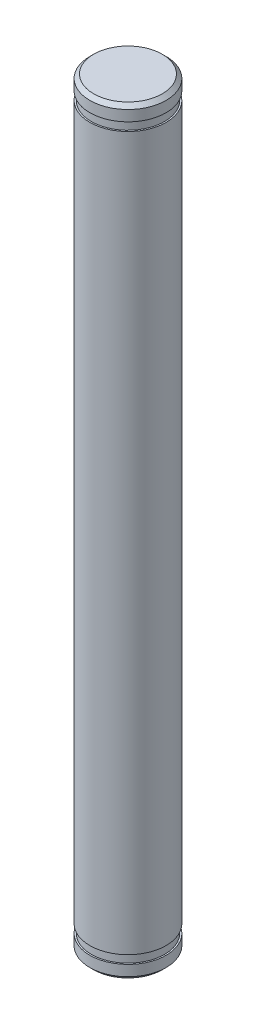
SolidWorks part; units mm, degrees
ref_plane "前视基准面" through (0, 0, 0) normal (0, 0, 1) x (1, 0, 0)
ref_plane "上视基准面" through (0, 0, 0) normal (0, 1, 0) x (1, 0, 0)
ref_plane "右视基准面" through (0, 0, 0) normal (1, 0, 0) x (0, 0, -1)
other "Configuration Table"
sketch "草图1" plane through (0, 0, 0) normal (0, 1, 0) x (1, 0, 0)
  circle A0 centre (0, 0) radius 5
  dimension "D1" = 10
extrude "凸台-拉伸1" add sketch "草图1" along normal blind 99.5
chamfer "倒角1" distance 0.5 angle 45 2 edges at (0, 0, 5) (0, 99.5, 5)
ref_plane "基准面1" through (0, 49.75, 0) normal (0, 1, 0) x (1, 0, 0)
sketch "草图2" plane through (0, 99.5, 0) normal (0, 1, 0) x (1, 0, 0)
  circle A0 centre (0, 0) radius 5 construction
  circle A1 centre (0, 0) radius 5
  circle A2 centre (0, 0) radius 4.8
  dimension "D1" = 9.6
extrude "切除-拉伸1" cut sketch "草图2" along normal blind 1.1 from offset 3 offset against normal yes
mirror "镜向1" about plane through (0, 49.75, 0) normal (0, 1, 0) of "切除-拉伸1"
